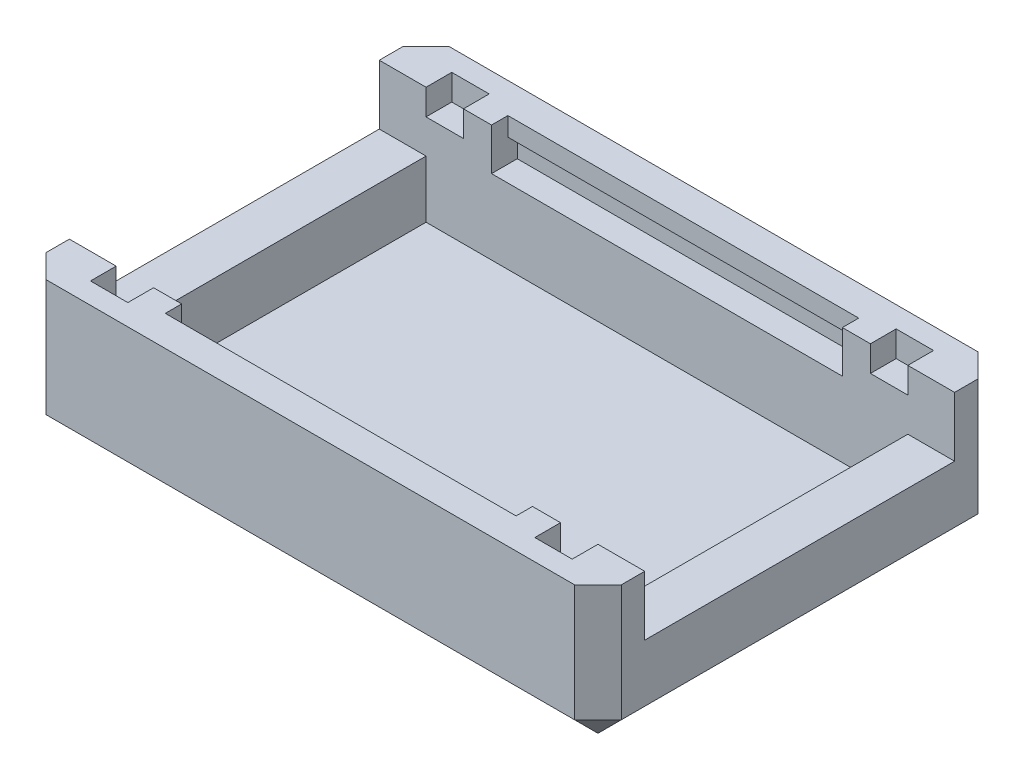
SolidWorks part; units mm, degrees
ref_plane "Front Plane" through (0, 0, 0) normal (0, 0, 1) x (1, 0, 0)
ref_plane "Top Plane" through (0, 0, 0) normal (0, 1, 0) x (1, 0, 0)
ref_plane "Right Plane" through (0, 0, 0) normal (1, 0, 0) x (0, 0, -1)
sketch "Sketch1" plane through (0, 0, 0) normal (0, 1, 0) x (1, 0, 0)
  line L0 (-12.3, -8.625) -> (-12.3, 8.625)
  line L1 (10.3, -6.625) -> (-10.3, -6.625)
  line L2 (10.3, -6.625) -> (10.3, 6.625)
  line L3 (10.3, 6.625) -> (-10.3, 6.625)
  line L4 (-10.3, -6.625) -> (-10.3, 6.625)
  line L5 (10.3, -6.625) -> (-10.3, 6.625) construction
  line L6 (10.3, 6.625) -> (-10.3, -6.625) construction
  line L11 (12.3, 8.625) -> (-12.3, 8.625)
  line L12 (12.3, -8.625) -> (12.3, 8.625)
  line L13 (12.3, -8.625) -> (-12.3, -8.625)
  point P0 (0, 0)
  dimension "D2" = 20.6
  dimension "D3" = 13.25
  dimension "D1" = 2
extrude "Boss-Extrude1" add sketch "Sketch1" along normal blind 6
sketch "Sketch2" plane through (0, 0, 0) normal (0, -1, 0) x (1, 0, 0)
  line L0 (10.3, 6.625) -> (10.3, -6.625) construction
  line L1 (-10.3, 6.625) -> (10.3, 6.625) construction
  line L2 (10.3, 6.625) -> (10.3, -6.625)
  line L3 (-10.3, 6.625) -> (10.3, 6.625)
  line L4 (10.3, -6.625) -> (-10.3, -6.625) construction
  line L5 (-10.3, -6.625) -> (-10.3, 6.625) construction
  line L6 (10.3, -6.625) -> (-10.3, -6.625)
  line L7 (-10.3, -6.625) -> (-10.3, 6.625)
extrude "Boss-Extrude2" add sketch "Sketch2" against normal blind 1
sketch "Sketch3" plane through (0, 6, 0) normal (0, 1, 0) x (1, 0, 0)
  line L0 (-12.3, 8.625) -> (-12.3, -8.625) construction
  line L1 (-10.3, 6.625) -> (-12.3, 6.625)
  line L2 (-10.3, 6.625) -> (-10.3, -6.625)
  line L3 (-10.3, -6.625) -> (-12.3, -6.625)
  line L4 (-12.3, 6.625) -> (-12.3, -6.625)
  line L5 (10.3, -6.625) -> (10.3, 6.625) construction
  line L6 (10.3, 6.625) -> (12.3, 6.625)
  line L7 (10.3, 6.625) -> (10.3, -6.625)
  line L8 (10.3, -6.625) -> (12.3, -6.625)
  line L9 (12.3, 6.625) -> (12.3, -6.625)
  line L10 (12.3, -8.625) -> (12.3, 8.625) construction
  line L11 (-10.3, -6.625) -> (10.3, -6.625) construction
  point P15 (0, 0)
extrude "Cut-Extrude1" cut sketch "Sketch3" against normal offset from surface (2.55 mm away) 2.45 up to face at (0, 1, 0)
sketch "Sketch4" plane through (0, 6, 0) normal (0, 1, 0) x (1, 0, 0)
  line L1 (-10.3, 6.625) -> (-8.7, 6.625)
  line L2 (-10.3, 6.625) -> (-10.3, 7.725)
  line L3 (-10.3, 7.725) -> (-8.7, 7.725)
  line L4 (-8.7, 6.625) -> (-8.7, 7.725)
  line L5 (10.3, 6.625) -> (8.7, 6.625)
  line L6 (10.3, 6.625) -> (10.3, 7.725)
  line L7 (10.3, 7.725) -> (8.7, 7.725)
  line L8 (8.7, 6.625) -> (8.7, 7.725)
  line L9 (10.3, -6.625) -> (8.7, -6.625)
  line L10 (10.3, -6.625) -> (10.3, -7.725)
  line L11 (10.3, -7.725) -> (8.7, -7.725)
  line L12 (8.7, -6.625) -> (8.7, -7.725)
  line L13 (-10.3, -6.625) -> (-8.7, -6.625)
  line L14 (-10.3, -6.625) -> (-10.3, -7.725)
  line L15 (-10.3, -7.725) -> (-8.7, -7.725)
  line L16 (-8.7, -6.625) -> (-8.7, -7.725)
  dimension "D1" = 1.1
  dimension "D2" = 1.6
extrude "Cut-Extrude2" cut sketch "Sketch4" against normal blind 1.1
sketch "Sketch5" plane through (0, 6, 0) normal (0, 1, 0) x (1, 0, 0)
  line L0 (-10.3, 6.625) -> (10.3, 6.625) construction
  line L1 (7.5, 7.325) -> (-7.5, 7.325)
  line L2 (7.5, 7.325) -> (7.5, 5.925)
  line L3 (7.5, 5.925) -> (-7.5, 5.925)
  line L4 (-7.5, 7.325) -> (-7.5, 5.925)
  line L5 (7.5, 7.325) -> (-7.5, 5.925) construction
  line L6 (7.5, 5.925) -> (-7.5, 7.325) construction
  line L7 (-8.7, -6.625) -> (8.7, -6.625) construction
  line L8 (7.5, -7.325) -> (-7.5, -7.325)
  line L9 (7.5, -7.325) -> (7.5, -5.925)
  line L10 (7.5, -5.925) -> (-7.5, -5.925)
  line L11 (-7.5, -7.325) -> (-7.5, -5.925)
  line L12 (7.5, -7.325) -> (-7.5, -5.925) construction
  line L13 (7.5, -5.925) -> (-7.5, -7.325) construction
  line L14 (12.3, 8.625) -> (-12.3, 8.625) construction
  point P0 (0, 6.625)
  point P7 (0, -6.625)
  dimension "D1" = 15
  dimension "D2" = 1.3
extrude "Cut-Extrude3" cut sketch "Sketch5" against normal blind 1.8
sketch "Sketch6" plane through (0, 0, -7.325) normal (0, 0, 1) x (1, 0, 0)
  line L0 (7.5, 4.2) -> (7.5, 6) construction
  line L1 (-7.5, 4.2) -> (7.5, 4.2)
  line L2 (-7.5, 4.2) -> (-7.5, 5.2)
  line L3 (-7.5, 5.2) -> (7.5, 5.2)
  line L4 (7.5, 4.2) -> (7.5, 5.2)
  dimension "D1" = 1
extrude "Cut-Extrude4" cut sketch "Sketch6" against normal blind 0.4
mirror "Mirror1" about plane through (0, 0, 0) normal (0, 0, 1) of "Cut-Extrude4"
chamfer "Chamfer1" distance 1 angle 45 8 edges at (12.3, 3, 8.625) (12.3, 0, 0) (12.3, 3, -8.625) (0, 0, 8.625) (-12.3, 3, 8.625) (-12.3, 3, -8.625) (0, 0, -8.625) (-12.3, 0, 0)
sketch "Sketch8" plane through (0, 0, 0) normal (0, -1, 0) x (1, 0, 0)
  line L0 (-5.3235, 2.4333) -> (5.3235, 2.4333) construction
  line L1 (-7.4119, -3.6511) -> (7.4119, -3.6511) construction
  text T0 "SWD" font "Century Gothic" height in points 10
  text T1 "ISOLATOR" font "Century Gothic" height in points 8
  point P4 (0, 2.4333)
  point P5 (0, -3.6511)
  point P6 (0, 0)
  point P8 (0, 0)
  point P9 (0, 0)
  point P11 (-5.3235, 2.4333)
extrude "Cut-Extrude5" cut sketch "Sketch8" against normal blind 0.2
